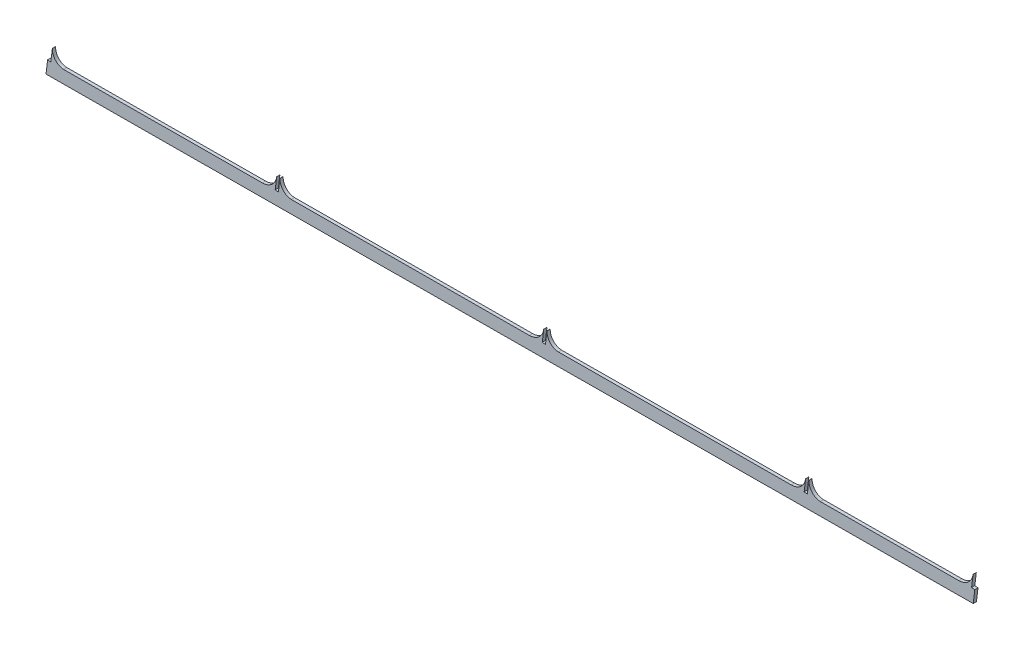
SolidWorks part; units mm, degrees
ref_plane "前视基准面" through (0, 0, 0) normal (0, 0, 1) x (1, 0, 0)
ref_plane "上视基准面" through (0, 0, 0) normal (0, 1, 0) x (1, 0, 0)
ref_plane "右视基准面" through (0, 0, 0) normal (1, 0, 0) x (0, 0, -1)
sketch "Model" plane through (0, 0, 0) normal (0, 0, 1) x (1, 0, 0)
  line L0 (4.1376, 9.8478) -> (580.8731, 12.9956)
  line L1 (7.1252, 17.7991) -> (5.1438, 18.0424)
  line L2 (148.6837, 18.5718) -> (146.7023, 18.815)
  line L3 (314.8061, 19.4785) -> (312.8247, 19.7217)
  line L4 (477.6903, 20.3675) -> (475.709, 20.6108)
  line L5 (581.8481, 20.936) -> (579.8667, 21.1792)
  line L6 (8.1001, 25.7395) -> (7.1252, 17.7991)
  line L7 (5.1438, 18.0424) -> (4.1376, 9.8478)
  line L8 (147.646, 26.5011) -> (146.7023, 18.815)
  line L9 (148.6837, 18.5718) -> (149.6586, 26.5121)
  line L10 (313.7684, 27.4078) -> (312.8247, 19.7217)
  line L11 (314.8061, 19.4785) -> (315.781, 27.4188)
  line L12 (476.6527, 28.2969) -> (475.709, 20.6108)
  line L13 (477.6903, 20.3675) -> (478.6653, 28.3078)
  line L14 (580.8104, 28.8653) -> (579.8667, 21.1792)
  line L15 (581.8481, 20.936) -> (580.8731, 12.9956)
  line L16 (15.125, 17.8428) -> (138.6712, 18.5171)
  line L17 (156.6836, 18.6154) -> (304.7936, 19.4238)
  line L18 (322.8059, 19.5221) -> (467.6779, 20.3128)
  line L19 (485.6902, 20.4111) -> (571.9121, 20.8814)
  arc A0 (8.1001, 25.7395) -> (15.125, 17.8428) centre (15.5451, 25.2895) ccw
  arc A1 (149.6586, 26.5121) -> (156.6836, 18.6154) centre (157.1036, 26.0621) ccw
  arc A2 (315.781, 27.4188) -> (322.8059, 19.5221) centre (323.2259, 26.9688) ccw
  arc A3 (478.6653, 28.3078) -> (485.6902, 20.4111) centre (486.1102, 27.8578) ccw
  arc A4 (138.6712, 18.5171) -> (147.646, 26.5011) centre (138.6986, 27.5226) ccw
  arc A5 (304.7936, 19.4238) -> (313.7684, 27.4078) centre (304.821, 28.4293) ccw
  arc A6 (467.6779, 20.3128) -> (476.6527, 28.2969) centre (467.7053, 29.3184) ccw
  arc A7 (571.9121, 20.8814) -> (580.8104, 28.8653) centre (571.863, 29.8868) ccw
extrude "凸台-拉伸1" add sketch "Model" along normal blind 2 contours A7 L19 A3 L13 L4 L12 A6 L18 A2 L11 L3 L10 A5 L17 A1 L9 L2 L8 A4 L16 A0 L6 L1 L7 L0 L15 L5 L14
